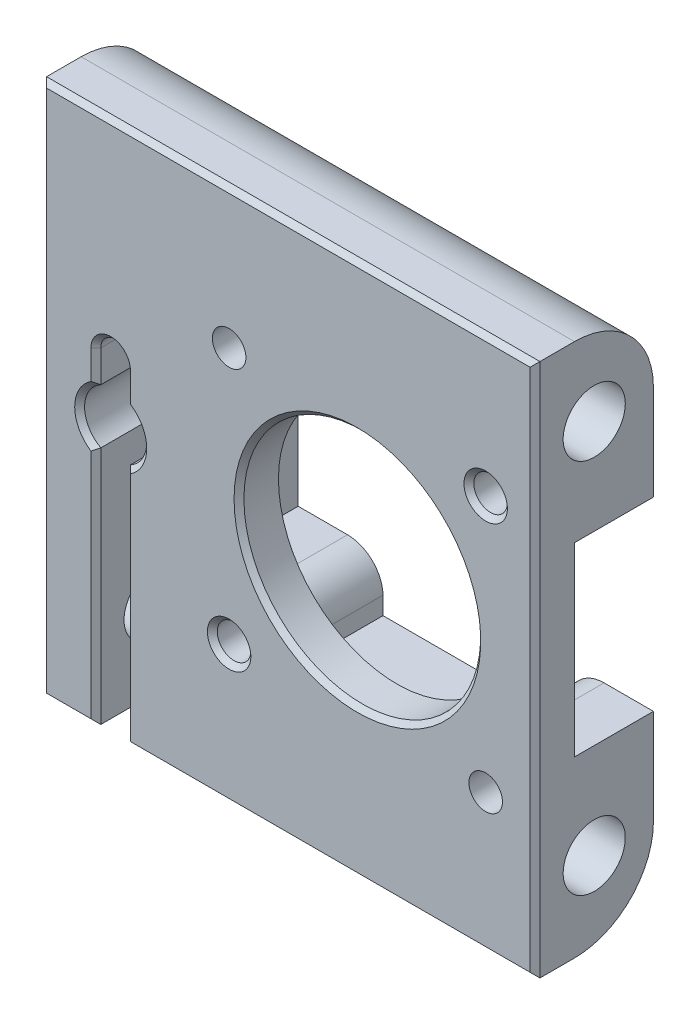
SolidWorks part; units mm, degrees
material "ABS"
ref_plane "Front Plane" through (0, 0, 0) normal (0, 0, 1) x (1, 0, 0)
ref_plane "Top Plane" through (0, 0, 0) normal (0, 1, 0) x (1, 0, 0)
ref_plane "Right Plane" through (0, 0, 0) normal (1, 0, 0) x (0, 0, -1)
sketch "Sketch1" plane through (0, 0, 0) normal (0, 0, 1) x (1, 0, 0)
  line L1 (0, 0) -> (50, 0)
  line L2 (0, 0) -> (0, 54.105)
  line L3 (0, 54.105) -> (50, 54.105)
  line L4 (50, 0) -> (50, 54.105)
  dimension "D1" = 54.105
  dimension "D2" = 50
extrude "Boss-Extrude1" add sketch "Sketch1" along normal blind 12
sketch "Sketch2" plane through (0, 0, 0) normal (1, 0, 0) x (0, 0, -1)
  line L0 (-12, 27.0525) -> (0, 27.0525) construction
  line L1 (-12, 0) -> (-12, 54.105) construction
  line L2 (0, 0) -> (0, 54.105) construction
  circle A0 centre (-6, 46.105) radius 3.15
  circle A1 centre (-6, 8) radius 3.15
  dimension "D2" = 6.3
  dimension "D1" = 6
  dimension "D3" = 19.0525
extrude "Cut-Extrude1" cut sketch "Sketch2" along normal through all
fillet "Fillet1" radius 8 2 edges at (25, 0, 0) (25, 54.105, 0)
sketch "Sketch3" plane through (0, 0, 0) normal (0, 0, -1) x (-1, 0, 0)
  line L0 (-50, 27.0525) -> (0, 27.0525) construction
  line L1 (-50, 8) -> (-50, 46.105) construction
  line L2 (0, 46.105) -> (0, 8) construction
  line L3 (-8.5, 0) -> (-8.5, 24.2826)
  line L5 (-5.5, 33.0525) -> (-5.5, 29.8224)
  line L6 (0, 0) -> (-50, 0) construction
  line L7 (-8.5, 0) -> (-5.5, 0)
  line L8 (-8.5, 29.8224) -> (-8.5, 33.0525)
  line L9 (-5.5, 24.2826) -> (-5.5, 0)
  arc A0 (-8.5, 29.8224) -> (-8.5, 24.2826) centre (-7, 27.0525) ccw
  circle A1 centre (-32, 27.0525) radius 12
  circle A2 centre (-19, 40.0525) radius 1.7
  circle A3 centre (-19, 14.0525) radius 1.7
  arc A4 (-5.5, 24.2826) -> (-5.5, 29.8224) centre (-7, 27.0525) ccw
  arc A5 (-5.5, 33.0525) -> (-8.5, 33.0525) centre (-7, 33.0525) ccw
  circle A6 centre (-45, 14.0525) radius 1.7
  circle A7 centre (-45, 40.0525) radius 1.7
  dimension "D1" = 24
  dimension "D2" = 6.3
  dimension "D5" = 3.4
  dimension "D6" = 1.5
  dimension "D7" = 13
  dimension "D10" = 13
  dimension "D3" = 7
  dimension "D4" = 25
  dimension "D8" = 3
  dimension "D9" = 6
  dimension "D11" = 4
extrude "Cut-Extrude2" cut sketch "Sketch3" against normal through all
sketch "Sketch5" plane through (0, 0, 0) normal (0, 0, -1) x (-1, 0, 0)
  line L0 (-50, 27.0525) -> (-29.1332, 27.0525) construction
  line L1 (-19, 17.6525) -> (-14, 17.6525)
  line L2 (-50, 36.4525) -> (-50, 17.6525)
  line L4 (-14, 36.4525) -> (-14, 17.6525)
  line L5 (-50, 8) -> (-50, 46.105) construction
  line L7 (0, 46.105) -> (0, 8) construction
  line L8 (-41.4013, 41.7525) -> (-22.5987, 41.7525)
  line L9 (-22.5987, 41.7525) -> (-22.5987, 39.955)
  line L10 (-41.4013, 39.955) -> (-41.4013, 41.7525)
  line L11 (-45, 36.4525) -> (-50, 36.4525)
  line L12 (-19, 36.4525) -> (-14, 36.4525)
  line L13 (-45, 17.6525) -> (-50, 17.6525)
  line L14 (-41.4013, 14.15) -> (-41.4013, 12.3525)
  line L15 (-22.5987, 12.3525) -> (-22.5987, 14.15)
  line L16 (-41.4013, 12.3525) -> (-22.5987, 12.3525)
  arc A0 (-45, 36.4525) -> (-41.4013, 39.955) centre (-45, 40.0525) ccw
  arc A1 (-22.5987, 39.955) -> (-19, 36.4525) centre (-19, 40.0525) ccw
  circle A2 centre (-45, 40.0525) radius 1.7 construction
  circle A3 centre (-19, 40.0525) radius 1.7 construction
  arc A4 (-22.5987, 14.15) -> (-19, 17.6525) centre (-19, 14.0525) cw
  arc A5 (-45, 17.6525) -> (-41.4013, 14.15) centre (-45, 14.0525) cw
  dimension "D5" = 3.6
  dimension "D4" = 14
extrude "Cut-Extrude4" cut sketch "Sketch5" against normal offset from surface (8 mm away) 4 up to face at (43.3, 40.0525, 12)
chamfer "Chamfer1" distance 0.5 angle 45 15 edges at (5.5, 12.1413, 12) (3.85, 27.0525, 12) (5.5, 31.4375, 12) (7, 34.5525, 12) (8.5, 31.4375, 12) (8.5, 12.1413, 12) (10.15, 27.0525, 12) (17.3, 14.0525, 12) (43.3, 40.0525, 12) (20, 27.0525, 12) (25, 54.105, 12) (0, 27.0525, 12) (2.75, 0, 12) (50, 27.0525, 12) (29.25, 0, 12)
